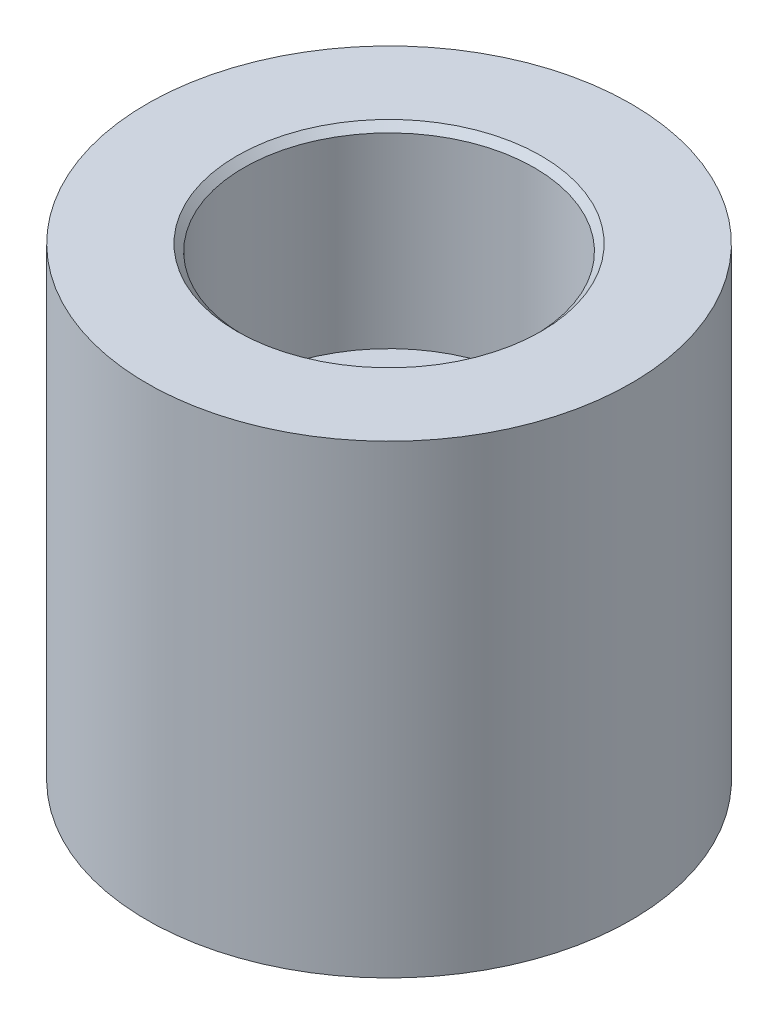
SolidWorks part; units mm, degrees
material "Cast Stainless Steel"
ref_plane "Front Plane" through (0, 0, 0) normal (0, 0, 1) x (1, 0, 0)
ref_plane "Top Plane" through (0, 0, 0) normal (0, 1, 0) x (1, 0, 0)
ref_plane "Right Plane" through (0, 0, 0) normal (1, 0, 0) x (0, 0, -1)
sketch "Sketch2" plane through (0, 0, 0) normal (0, 0, 1) x (1, 0, 0)
  line L0 (0, 0) -> (0, 102.9648) construction
  line L1 (0, 0) -> (25, 0)
  line L2 (25, 0) -> (25, 3.4197)
  line L3 (25, 3.4197) -> (25, 48)
  line L4 (25, 48) -> (15.7071, 48)
  line L5 (15, 47.2929) -> (15, 28)
  line L6 (15, 28) -> (0, 28)
  line L7 (0, 0) -> (0, 28)
  line L8 (15.7071, 48) -> (15, 47.2929)
  dimension "D1" = 25
  dimension "D2" = 48
  dimension "D3" = 15
  dimension "D5" = 45
  dimension "D6" = 1
revolve "Revolve1" add sketch "Sketch2" angle 360 about L0
sketch "Sketch4" plane through (0, 28, 0) normal (0, 1, 0) x (1, 0, 0)
  circle A0 centre (0, 0) radius 5
  dimension "D1" = 10
extrude "Cut-Extrude1" cut sketch "Sketch4" against normal blind 8
sketch "Sketch5" plane through (0, 20, 0) normal (0, 1, 0) x (1, 0, 0)
  circle A0 centre (0, 0) radius 3
  dimension "D1" = 6
extrude "Cut-Extrude2" cut sketch "Sketch5" against normal blind 48
sketch "Sketch6" plane through (0, 0, 0) normal (0, 0, 1) x (1, 0, 0)
  circle A0 centre (0, 24) radius 1
  dimension "D1" = 2
  dimension "D2" = 24
extrude "Cut-Extrude3" cut sketch "Sketch6" against normal blind 48
sketch3d "URDF Reference"
  line L0 (0, 0, 0) -> (10, 0, 0) construction
  line L1 (0, 0, 0) -> (0, 0, -10) construction
  point P0 (0, 0, 0)
  point P1 (0, 0, 0)
